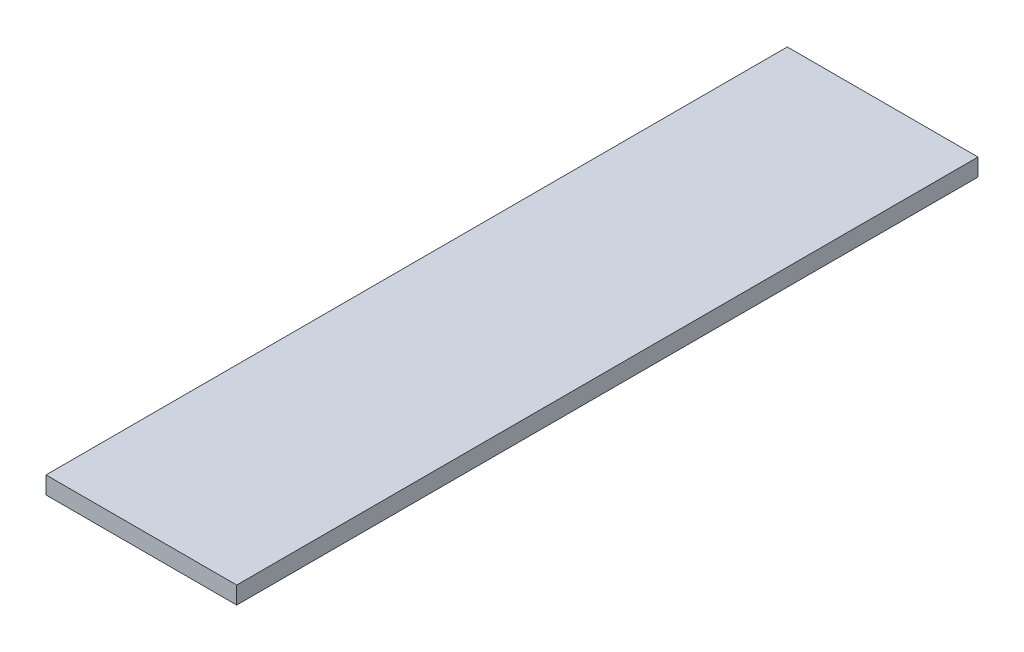
SolidWorks part; units mm, degrees
material "Pine"
ref_plane "Front Plane" through (0, 0, 0) normal (0, 0, 1) x (1, 0, 0)
ref_plane "Top Plane" through (0, 0, 0) normal (0, 1, 0) x (1, 0, 0)
ref_plane "Right Plane" through (0, 0, 0) normal (1, 0, 0) x (0, 0, -1)
sketch "Sketch1" plane through (0, 0, 0) normal (0, 0, 1) x (1, 0, 0)
  line L0 (-528.0858, 1862.9968) -> (-737.1845, 1862.9968)
  line L1 (-737.1845, 1862.9968) -> (-737.1845, 1843.9468)
  line L2 (-528.0858, 1862.9968) -> (-528.0858, 1843.9468)
  line L6 (-528.0858, 1843.9468) -> (-737.1845, 1843.9468)
  dimension "D1" = 19.05
extrude "Boss-Extrude1" add sketch "Sketch1" along normal blind 812.8
